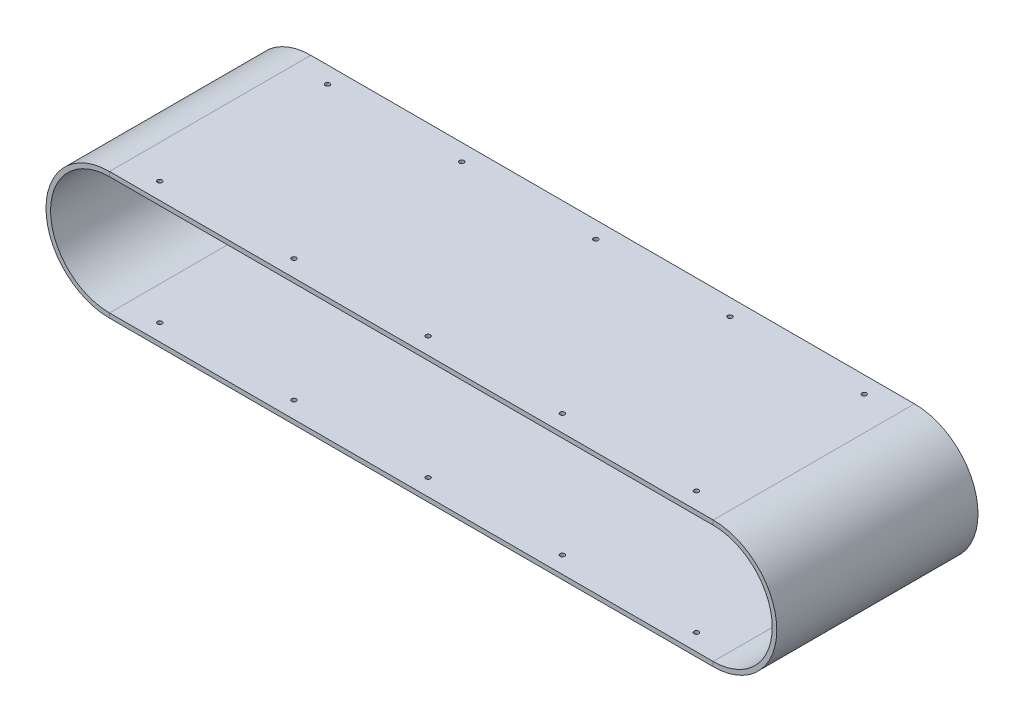
SolidWorks part; units mm, degrees
ref_plane "Front Plane" through (0, 0, 0) normal (0, 0, 1) x (1, 0, 0)
ref_plane "Top Plane" through (0, 0, 0) normal (0, 1, 0) x (1, 0, 0)
ref_plane "Right Plane" through (0, 0, 0) normal (1, 0, 0) x (0, 0, -1)
sketch "Sketch1" plane through (0, 0, 0) normal (0, 0, 1) x (1, 0, 0)
  line L0 (0, 46.3995) -> (457.2, 46.3995)
  line L1 (0, -46.3995) -> (457.2, -46.3995)
  line L2 (228.6, 46.3995) -> (228.6, -46.3995) construction
  arc A0 (0, 46.3995) -> (0, -46.3995) centre (0, 0) ccw
  arc A1 (457.2, 46.3995) -> (457.2, -46.3995) centre (457.2, 0) cw
  dimension "32" = 46.3995
  dimension "D1" = 457.2
sketch "Sketch2" plane through (0, 0, 0) normal (1, 0, 0) x (0, 0, -1)
  line L0 (0, 46.3995) -> (0, -46.3995) construction
  line L1 (-76.2, 44.685) -> (76.2, 44.685)
  line L2 (-76.2, 44.685) -> (-76.2, 48.114)
  line L3 (-76.2, 48.114) -> (76.2, 48.114)
  line L4 (76.2, 44.685) -> (76.2, 48.114)
  line L5 (-76.2, 44.685) -> (76.2, 48.114) construction
  line L6 (-76.2, 48.114) -> (76.2, 44.685) construction
  line L7 (0, 46.3995) -> (0, -46.3995) construction
  point P0 (0, 46.3995)
  dimension "D1" = 3.429
  dimension "D2" = 152.4
sweep "Sweep1" add profiles "Sketch2" path "Sketch1"
sketch "Sketch3" plane through (0, 48.114, 0) normal (0, 1, 0) x (1, 0, 0)
  line L0 (0, -63.5) -> (457.2, -63.5) construction
  line L1 (457.2, 76.2) -> (457.2, -76.2) construction
  line L2 (457.2, -76.2) -> (0, -76.2) construction
  line L3 (0, 76.2) -> (0, -76.2) construction
  line L4 (0, 0) -> (457.2, 0) construction
  circle A0 centre (25.4, -63.5) radius 1.75
  circle A1 centre (25.4, 63.5) radius 1.75
  circle A2 centre (127, -63.5) radius 1.75
  circle A3 centre (127, 63.5) radius 1.75
  circle A4 centre (228.6, -63.5) radius 1.75
  circle A5 centre (228.6, 63.5) radius 1.75
  circle A6 centre (330.2, -63.5) radius 1.75
  circle A7 centre (330.2, 63.5) radius 1.75
  circle A8 centre (431.8, -63.5) radius 1.75
  circle A9 centre (431.8, 63.5) radius 1.75
  circle A10 centre (533.4, -63.5) radius 1.75
  circle A11 centre (533.4, 63.5) radius 1.75
  dimension "D2" = 3.5
  dimension "D1" = 12.7
  dimension "D3" = 25.4
  dimension "D5" = 101.6
  dimension "D4" = 6
extrude "Cut-Extrude1" cut sketch "Sketch3" against normal through all
equation "\"D2@Sketch2\"=6in"
equation "\"32@Sketch1\"=1.75925+0.135/2in"
